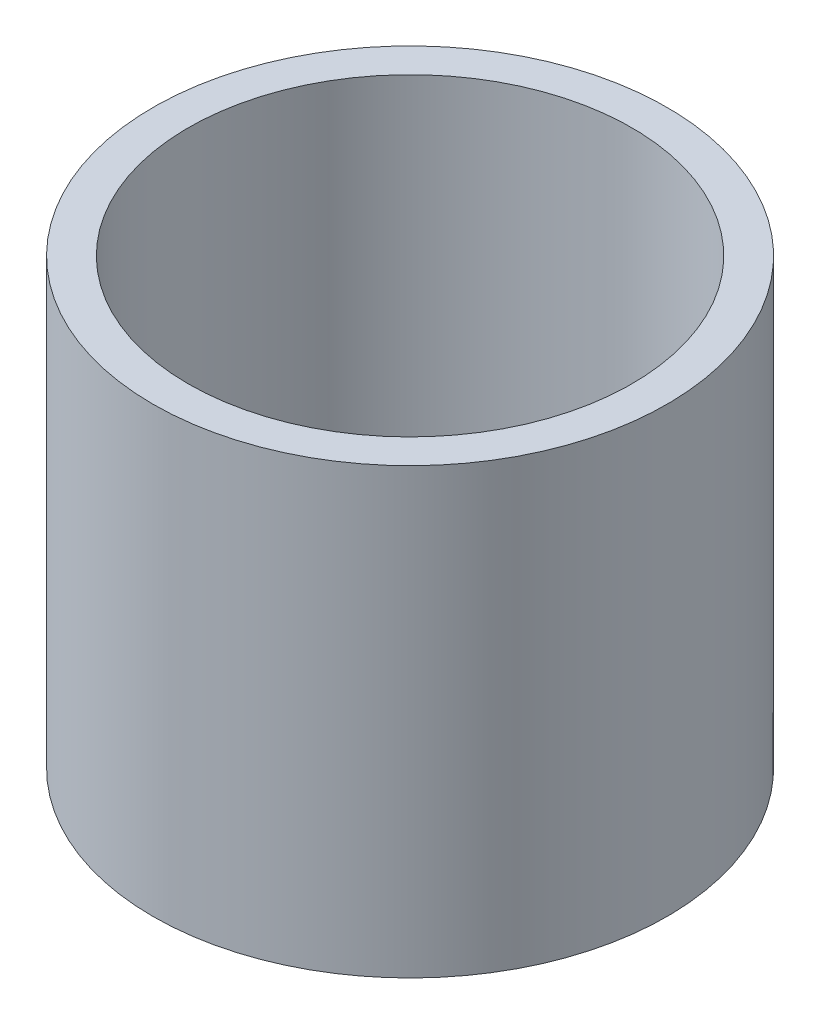
SolidWorks part; units mm, degrees
ref_plane "Front Plane" through (0, 0, 0) normal (0, 0, 1) x (1, 0, 0)
ref_plane "Top Plane" through (0, 0, 0) normal (0, 1, 0) x (1, 0, 0)
ref_plane "Right Plane" through (0, 0, 0) normal (1, 0, 0) x (0, 0, -1)
sketch "Sketch1" plane through (0, 0, 0) normal (0, 1, 0) x (1, 0, 0)
  circle A0 centre (0, 0) radius 20
  circle A1 centre (0, 0) radius 23.175
  dimension "D1" = 40
  dimension "D2" = 3.175
extrude "Boss-Extrude1" add sketch "Sketch1" along normal blind 40
